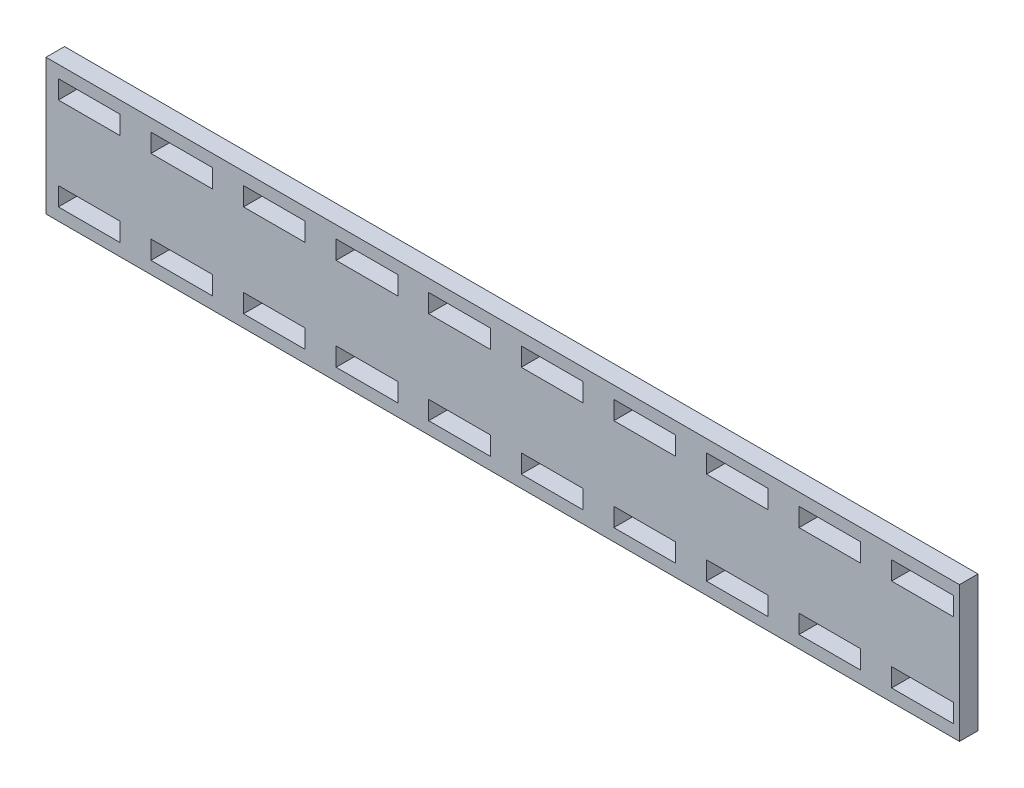
SolidWorks part; units mm, degrees
material "Thornel Mat VMA"
ref_plane "前视基准面" through (0, 0, 0) normal (0, 0, 1) x (1, 0, 0)
ref_plane "上视基准面" through (0, 0, 0) normal (0, 1, 0) x (1, 0, 0)
ref_plane "右视基准面" through (0, 0, 0) normal (1, 0, 0) x (0, 0, -1)
sketch "草图1" plane through (0, 0, 0) normal (0, 0, 1) x (1, 0, 0)
  line L0 (-57, 9) -> (-57, 6)
  line L1 (-74, 11) -> (74, 11)
  line L2 (-74, 11) -> (-74, -11)
  line L3 (-74, -11) -> (74, -11)
  line L4 (74, 11) -> (74, -11)
  line L5 (-74, 11) -> (74, -11) construction
  line L6 (-74, -11) -> (74, 11) construction
  line L7 (-72, 9) -> (-62, 9)
  line L8 (-72, 9) -> (-72, 6)
  line L9 (-72, 6) -> (-62, 6)
  line L10 (-62, 9) -> (-62, 6)
  line L11 (-57, 9) -> (-47, 9)
  line L12 (-47, 9) -> (-47, 6)
  line L13 (-57, 6) -> (-47, 6)
  line L14 (-42, 9) -> (-42, 6)
  line L15 (-42, 9) -> (-32, 9)
  line L16 (-32, 9) -> (-32, 6)
  line L17 (-42, 6) -> (-32, 6)
  line L18 (-27, 9) -> (-27, 6)
  line L19 (-27, 9) -> (-17, 9)
  line L20 (-17, 9) -> (-17, 6)
  line L21 (-27, 6) -> (-17, 6)
  line L22 (-12, 9) -> (-12, 6)
  line L23 (-12, 9) -> (-2, 9)
  line L24 (-2, 9) -> (-2, 6)
  line L25 (-12, 6) -> (-2, 6)
  line L26 (3, 9) -> (3, 6)
  line L27 (3, 9) -> (13, 9)
  line L28 (13, 9) -> (13, 6)
  line L29 (3, 6) -> (13, 6)
  line L30 (18, 9) -> (18, 6)
  line L31 (18, 9) -> (28, 9)
  line L32 (28, 9) -> (28, 6)
  line L33 (18, 6) -> (28, 6)
  line L34 (33, 9) -> (33, 6)
  line L35 (33, 9) -> (43, 9)
  line L36 (43, 9) -> (43, 6)
  line L37 (33, 6) -> (43, 6)
  line L38 (48, 9) -> (48, 6)
  line L39 (48, 9) -> (58, 9)
  line L40 (58, 9) -> (58, 6)
  line L41 (48, 6) -> (58, 6)
  line L42 (63, 9) -> (63, 6)
  line L43 (63, 9) -> (73, 9)
  line L44 (73, 9) -> (73, 6)
  line L45 (63, 6) -> (73, 6)
  line L46 (55, 0) -> (-55, 0) construction
  line L47 (63, -9) -> (73, -9)
  line L48 (73, -9) -> (73, -6)
  line L49 (63, -6) -> (73, -6)
  line L50 (63, -9) -> (63, -6)
  line L51 (48, -9) -> (58, -9)
  line L52 (58, -9) -> (58, -6)
  line L53 (48, -6) -> (58, -6)
  line L54 (48, -9) -> (48, -6)
  line L55 (33, -9) -> (43, -9)
  line L56 (43, -9) -> (43, -6)
  line L57 (33, -6) -> (43, -6)
  line L58 (33, -9) -> (33, -6)
  line L59 (18, -9) -> (28, -9)
  line L60 (28, -9) -> (28, -6)
  line L61 (18, -6) -> (28, -6)
  line L62 (18, -9) -> (18, -6)
  line L63 (3, -9) -> (13, -9)
  line L64 (13, -9) -> (13, -6)
  line L65 (3, -6) -> (13, -6)
  line L66 (3, -9) -> (3, -6)
  line L67 (-12, -9) -> (-2, -9)
  line L68 (-2, -9) -> (-2, -6)
  line L69 (-12, -6) -> (-2, -6)
  line L70 (-12, -9) -> (-12, -6)
  line L71 (-27, -9) -> (-17, -9)
  line L72 (-17, -9) -> (-17, -6)
  line L73 (-27, -6) -> (-17, -6)
  line L74 (-27, -9) -> (-27, -6)
  line L75 (-42, -9) -> (-32, -9)
  line L76 (-32, -9) -> (-32, -6)
  line L77 (-42, -6) -> (-32, -6)
  line L78 (-42, -9) -> (-42, -6)
  line L79 (-57, -9) -> (-47, -9)
  line L80 (-47, -9) -> (-47, -6)
  line L81 (-57, -6) -> (-47, -6)
  line L82 (-57, -9) -> (-57, -6)
  line L83 (-72, -6) -> (-62, -6)
  line L84 (-62, -9) -> (-62, -6)
  line L85 (-72, -9) -> (-62, -9)
  line L86 (-72, -9) -> (-72, -6)
  point P0 (0, 0)
  dimension "D1" = 148
  dimension "D2" = 22
  dimension "D3" = 10
  dimension "D4" = 3
  dimension "D5" = 2
  dimension "D6" = 2
  dimension "D7" = 10
extrude "凸台-拉伸1" add sketch "草图1" along normal blind 3
